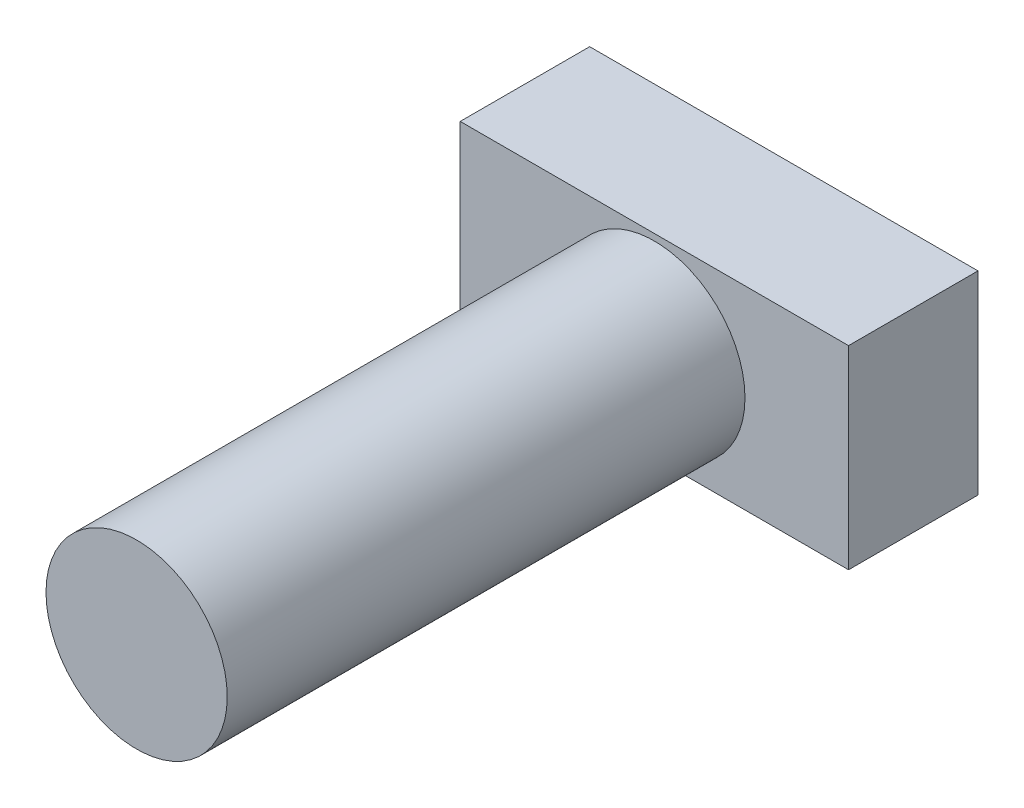
SolidWorks part; units mm, degrees
ref_plane "Front Plane" through (0, 0, 0) normal (0, 0, 1) x (1, 0, 0)
ref_plane "Top Plane" through (0, 0, 0) normal (0, 1, 0) x (1, 0, 0)
ref_plane "Right Plane" through (0, 0, 0) normal (1, 0, 0) x (0, 0, -1)
sketch "Sketch1" plane through (0, 0, 0) normal (0, 0, 1) x (1, 0, 0)
  circle A0 centre (0, 0) radius 7
  dimension "D1" = 14
extrude "Boss-Extrude1" add sketch "Sketch1" along normal blind 40
sketch "Sketch2" plane through (0, 0, 0) normal (0, 0, -1) x (-1, 0, 0)
  line L1 (-15, -7.5) -> (15, -7.5)
  line L2 (-15, -7.5) -> (-15, 7.5)
  line L3 (-15, 7.5) -> (15, 7.5)
  line L4 (15, -7.5) -> (15, 7.5)
  line L5 (-15, -7.5) -> (15, 7.5) construction
  line L6 (-15, 7.5) -> (15, -7.5) construction
  point P0 (0, 0)
  dimension "D1" = 30
  dimension "D2" = 15
extrude "Boss-Extrude2" add sketch "Sketch2" along normal blind 10
